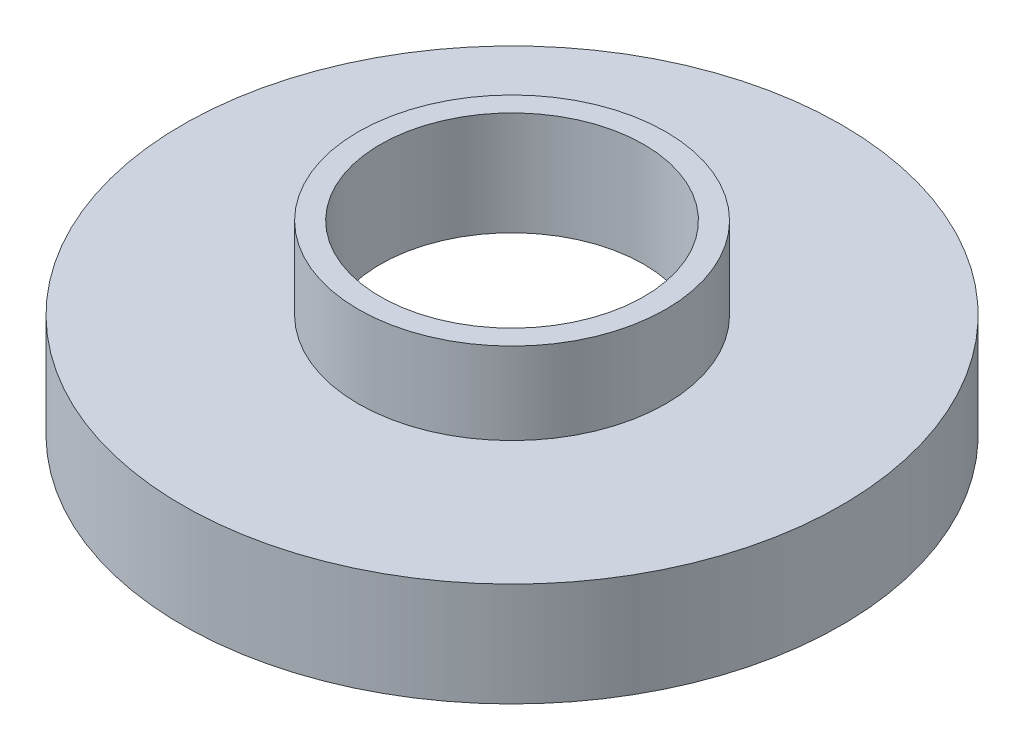
SolidWorks part; units mm, degrees
ref_plane "Front Plane" through (0, 0, 0) normal (0, 0, 1) x (1, 0, 0)
ref_plane "Top Plane" through (0, 0, 0) normal (0, 1, 0) x (1, 0, 0)
ref_plane "Right Plane" through (0, 0, 0) normal (1, 0, 0) x (0, 0, -1)
sketch "Sketch1" plane through (0, 0, 0) normal (0, 0, 1) x (1, 0, 0)
  line L0 (0, 0) -> (0, 26.3547) construction
  line L2 (19.05, 26.825) -> (19.05, 11.825)
  line L3 (19.05, 11.825) -> (44.45, 11.825)
  line L4 (44.45, 11.825) -> (44.45, 0)
  line L5 (44.45, 0) -> (47.625, 0)
  line L6 (47.625, 0) -> (47.625, 15)
  line L7 (47.625, 15) -> (22.225, 15)
  line L8 (22.225, 15) -> (22.225, 26.825)
  line L9 (22.225, 26.825) -> (19.05, 26.825)
  line L10 (55, 0) -> (-55, 0) construction
  dimension "D1" = 3.175
  dimension "D2" = 3.175
  dimension "D3" = 3.175
  dimension "D4" = 15
  dimension "D6" = 15
  dimension "D7" = 19.05
  dimension "3.5in/2" = 47.625
revolve "Revolve1" add sketch "Sketch1" angle 360 about L0
